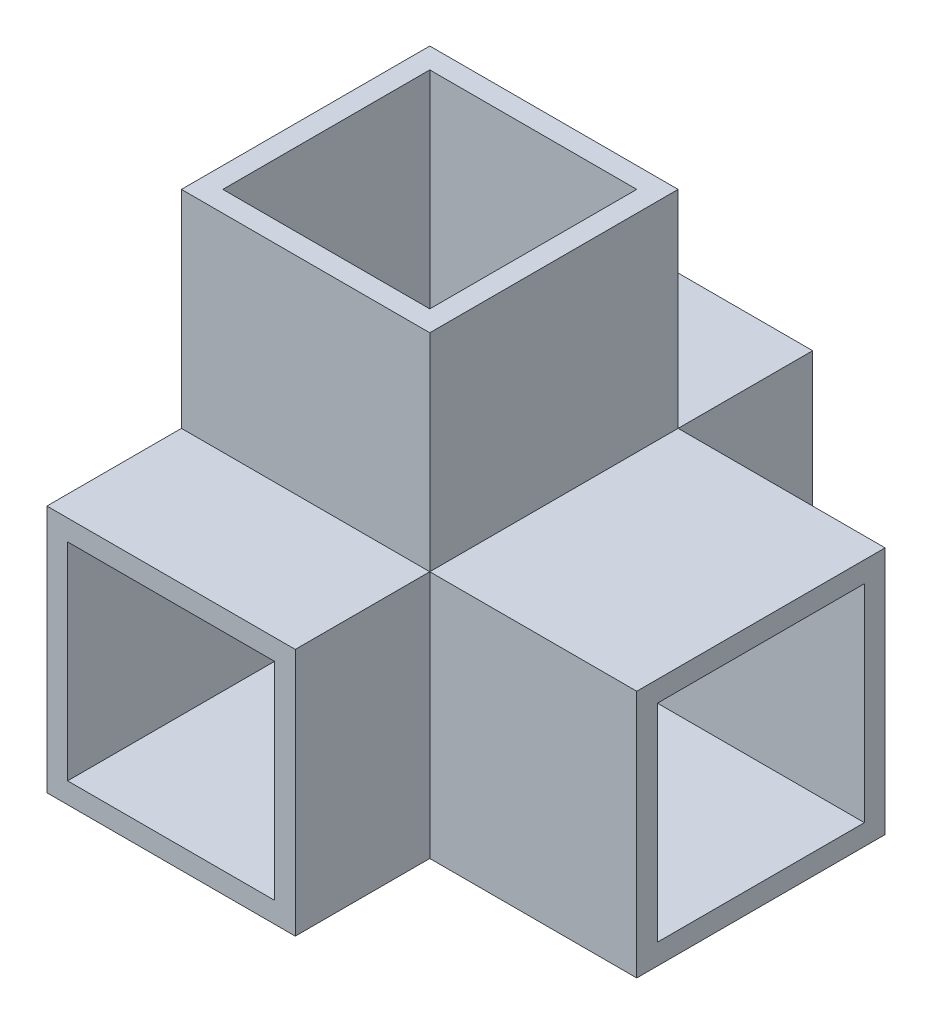
SolidWorks part; units mm, degrees
ref_plane "前视基准面" through (0, 0, 0) normal (0, 0, 1) x (1, 0, 0)
ref_plane "上视基准面" through (0, 0, 0) normal (0, 1, 0) x (1, 0, 0)
ref_plane "右视基准面" through (0, 0, 0) normal (1, 0, 0) x (0, 0, -1)
sketch "草图2" plane through (0, 0, 0) normal (0, 0, 1) x (1, 0, 0)
  line L0 (-107.8441, 0) -> (83.7115, 0) construction
  line L2 (0, 55.9754) -> (0, -54.6913) construction
  line L3 (-24, 24) -> (24, 24)
  line L4 (-24, 24) -> (-24, -24)
  line L5 (-24, -24) -> (24, -24)
  line L6 (24, 24) -> (24, -24)
  line L7 (-20, 20) -> (20, 20)
  line L8 (-20, 20) -> (-20, -20)
  line L9 (-20, -20) -> (20, -20)
  line L10 (20, 20) -> (20, -20)
  dimension "D1" = 48
  dimension "D2" = 48
  dimension "D3" = 40
  dimension "D4" = 40
extrude "凸台-拉伸1" add sketch "草图2" along normal blind 100
sketch "草图3" plane through (24, 0, 0) normal (1, 0, 0) x (0, 0, -1)
  line L0 (-100, 24) -> (0, 24) construction
  line L1 (-74, 24) -> (-26, 24)
  line L2 (-74, 24) -> (-74, -24)
  line L3 (-74, -24) -> (-26, -24)
  line L4 (-26, 24) -> (-26, -24)
  line L5 (-100, -24) -> (0, -24) construction
  line L6 (-100, -24) -> (-100, 24) construction
  line L8 (-70, 20) -> (-30, 20)
  line L9 (-70, 20) -> (-70, -20)
  line L10 (-70, -20) -> (-30, -20)
  line L11 (-30, 20) -> (-30, -20)
  dimension "D1" = 48
  dimension "D2" = 26
  dimension "D3" = 4
  dimension "D4" = 4
  dimension "D5" = 4
  dimension "D6" = 4
extrude "凸台-拉伸2" add sketch "草图3" along normal blind 40
sketch "草图4" plane through (0, 24, 0) normal (0, 1, 0) x (1, 0, 0)
  line L0 (-24, -100) -> (-24, 0) construction
  line L1 (24, -26) -> (-24, -26)
  line L2 (24, -26) -> (24, -74)
  line L3 (24, -74) -> (-24, -74)
  line L4 (-24, -26) -> (-24, -74)
  line L6 (-20, -30) -> (20, -30)
  line L7 (-20, -30) -> (-20, -70)
  line L8 (-20, -70) -> (20, -70)
  line L9 (20, -30) -> (20, -70)
  dimension "D1" = 4
  dimension "D2" = 4
  dimension "D3" = 40
  dimension "D4" = 4
extrude "凸台-拉伸3" add sketch "草图4" along normal blind 40
